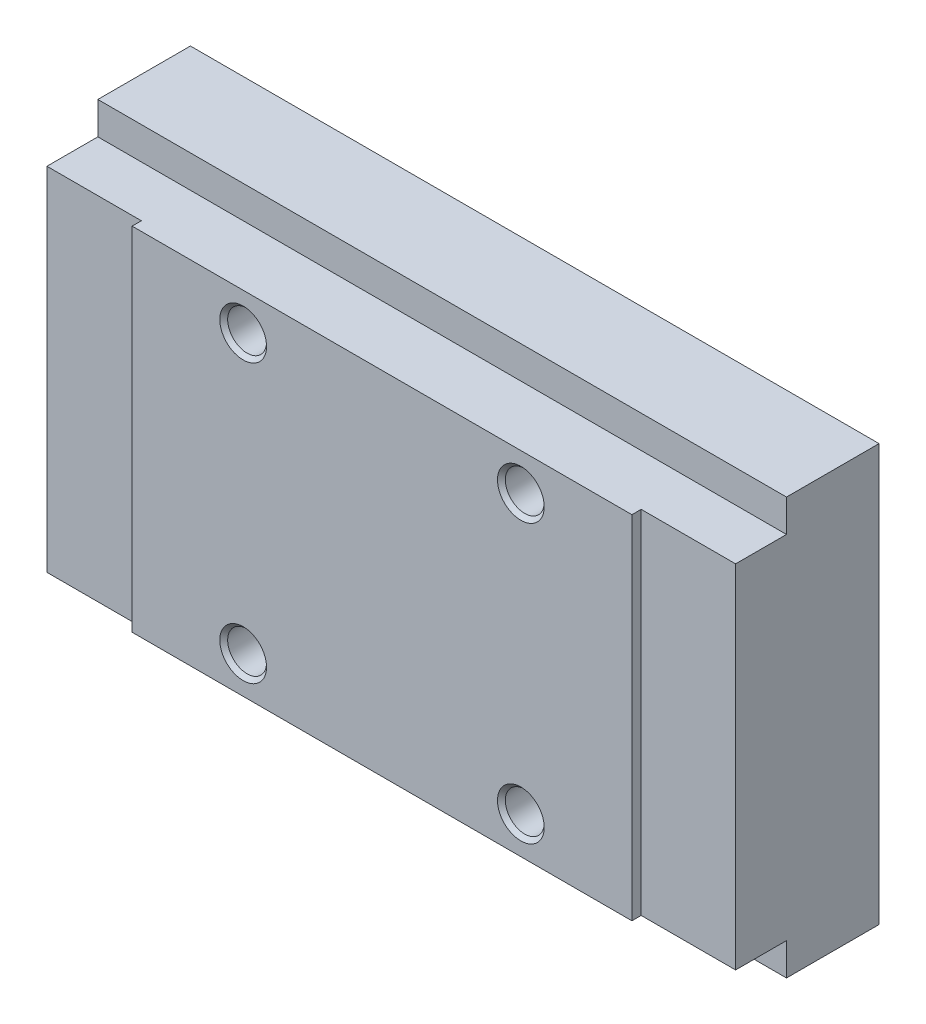
SolidWorks part; units mm, degrees
ref_plane "前视基准面" through (0, 0, 0) normal (0, 0, 1) x (1, 0, 0)
ref_plane "上视基准面" through (0, 0, 0) normal (0, 1, 0) x (1, 0, 0)
ref_plane "右视基准面" through (0, 0, 0) normal (1, 0, 0) x (0, 0, -1)
other "Configuration Table"
sketch "草图1" plane through (0, 0, 0) normal (0, 0, 1) x (1, 0, 0)
  line L1 (0, 0) -> (74.4, 0)
  line L2 (0, 0) -> (0, -45)
  line L3 (0, -45) -> (74.4, -45)
  line L4 (74.4, 0) -> (74.4, -45)
  dimension "D1" = 74.4
  dimension "D2" = 45
extrude "凸台-拉伸1" add sketch "草图1" along normal blind 10
sketch "草图2" plane through (0, 0, 10) normal (0, 0, 1) x (1, 0, 0)
  line L0 (0, 0) -> (0, -45) construction
  line L1 (0, -3.5) -> (74.4, -3.5)
  line L2 (0, -3.5) -> (0, -41.5)
  line L3 (0, -41.5) -> (74.4, -41.5)
  line L4 (74.4, -3.5) -> (74.4, -41.5)
  line L5 (74.4, -45) -> (74.4, 0) construction
  line L6 (0, -45) -> (74.4, -45) construction
  dimension "D1" = 38
  dimension "D2" = 3.5
extrude "凸台-拉伸2" add sketch "草图2" along normal blind 6.5
hole_wizard "M5 螺纹孔1" positions "草图3" profile "草图4" tap size "M5" standard "GB"
sketch "草图3" plane through (0, 0, 16.5) normal (0, 0, 1) x (1, 0, 0)
  line L0 (0, -3.5) -> (0, -41.5) construction
  line L1 (74.4, 0) -> (0, 0) construction
  point P0 (22.2, -7.5)
  point P12 (52.2, -7.5)
  point P13 (52.2, -37.5)
  point P14 (22.2, -37.5)
  dimension "D1" = 22.2
  dimension "D2" = 7.5
  dimension "D3" = 2
  dimension "D4" = 2
sketch "草图4" plane through (22.2, -7.5, 16.5) normal (1, 0, 0) x (0, -1, 0)
  line L0 (0, 0) -> (0, 13.6618)
  line L1 (0, 13.6618) -> (2.1, 12.4)
  line L2 (2.1, 12.4) -> (2.1, 0.425)
  line L3 (2.1, 0.425) -> (2.525, 0)
  line L5 (2.525, 0) -> (0, 0)
  line L6 (-2.1, 0.425) -> (-2.525, 0) construction
  line L10 (0, 13.6618) -> (-2.1, 12.4) construction
  line L11 (0, -6.35) -> (0, 107.95) construction
  dimension "螺纹孔钻头直径" = 4.2
  dimension "螺纹孔钻头深度" = 12.4
  dimension "近端锥形沉头孔直径" = 5.05
  dimension "近端锥形沉头孔角度" = 90
  dimension "导头角度" = 118
cosmetic thread "孔螺蚊线1"
cosmetic thread "孔螺蚊线2"
cosmetic thread "孔螺蚊线3"
cosmetic thread "孔螺蚊线4"
sketch "草图5" plane through (0, 0, 16.5) normal (0, 0, 1) x (1, 0, 0)
  line L0 (74.4, -3.5) -> (0, -3.5) construction
  line L1 (10.2, -3.5) -> (64.2, -3.5)
  line L2 (10.2, -3.5) -> (10.2, -41.5)
  line L3 (10.2, -41.5) -> (64.2, -41.5)
  line L4 (64.2, -3.5) -> (64.2, -41.5)
  line L5 (0, -41.5) -> (74.4, -41.5) construction
  line L6 (0, -3.5) -> (0, -41.5) construction
  dimension "D1" = 54
  dimension "D2" = 10.2
extrude "切除-拉伸1" cut sketch "草图5" against normal blind 1 flip side to cut
